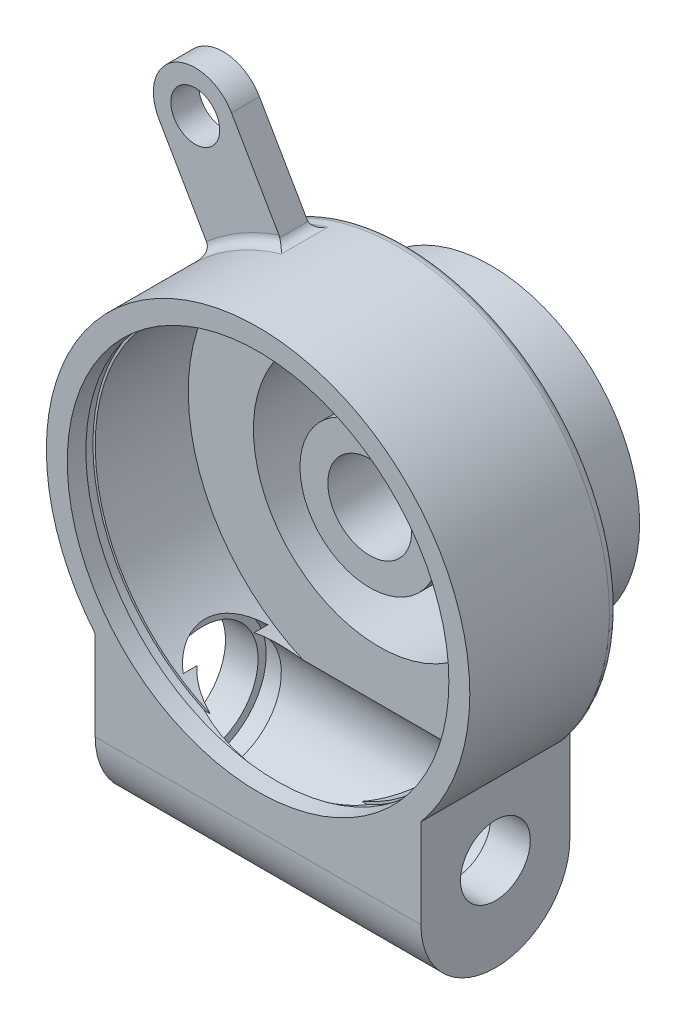
SolidWorks part; units mm, degrees
ref_plane "前视基准面" through (0, 0, 0) normal (0, 0, 1) x (1, 0, 0)
ref_plane "上视基准面" through (0, 0, 0) normal (0, 1, 0) x (1, 0, 0)
ref_plane "右视基准面" through (0, 0, 0) normal (1, 0, 0) x (0, 0, -1)
sketch "草图1" plane through (0, 0, 0) normal (0, 0, 1) x (1, 0, 0)
  circle A0 centre (0, 0) radius 45.5
  dimension "D1" = 91
extrude "凸台-拉伸1" add sketch "草图1" against normal blind 32
sketch "草图2" plane through (0, 0, -32) normal (0, 0, -1) x (-1, 0, 0)
  circle A0 centre (0, 0) radius 32
  dimension "D1" = 64
extrude "凸台-拉伸2" add sketch "草图2" along normal blind 18
sketch "草图3" plane through (0, 0, 0) normal (0, 0, 1) x (1, 0, 0)
  line L0 (0, 0) -> (-33.5, 58.0237) construction
  line L1 (-7.7942, -4.5) -> (-41.2942, 53.5237)
  line L2 (7.7942, 4.5) -> (-25.7058, 62.5237)
  line L3 (0, 0) -> (0, 77.4343) construction
  arc A0 (-7.7942, -4.5) -> (7.7942, 4.5) centre (0, 0) ccw
  arc A1 (-25.7058, 62.5237) -> (-41.2942, 53.5237) centre (-33.5, 58.0237) ccw
  arc A2 (-30.0947, 34.1256) -> (-14.5063, 43.1256) centre (0, 0) cw
  circle A3 centre (0, 0) radius 45.5 construction
  point P3 (-16.75, 29.0119)
  circle M3 centre (0, 0) radius 45.5
  dimension "D2" = 9
  dimension "D1" = 30
  dimension "D3" = 67
extrude "凸台-拉伸3" add sketch "草图3" along normal blind 6 from offset 26 contours L2 A1 L1 M3 offset against normal yes
sketch "草图4" plane through (0, 0, -20) normal (0, 0, 1) x (1, 0, 0)
  circle A0 centre (-33.5, 58.0237) radius 5.25
  dimension "D1" = 10.5
extrude "切除-拉伸1" cut sketch "草图4" against normal through all
sketch "草图5" plane through (0, 0, 0) normal (1, 0, 0) x (0, 0, -1)
  line L0 (16, -45.5) -> (16, -48.25) construction
  line L1 (0, -45.5) -> (32, -45.5) construction
  line L2 (32, -48.25) -> (16, -48.25) construction
  line L3 (32, -48.25) -> (32, -0.1888)
  line L4 (0, -48.25) -> (0, -0.1888)
  line L5 (32, -0.1888) -> (0, -0.1888)
  line L6 (16, -48.25) -> (0, -48.25) construction
  arc A0 (0, -48.25) -> (32, -48.25) centre (16, -48.25) ccw
  arc A1 (32, -48.25) -> (0, -48.25) centre (16, -48.25) ccw construction
  dimension "D1" = 32
  dimension "D2" = 48.25
extrude "凸台-拉伸4" add sketch "草图5" along normal mid plane 70
sketch "草图6" plane through (0, 0, 0) normal (0, 0, 1) x (1, 0, 0)
  circle A0 centre (0, 0) radius 41
  point P0 (0, 0)
  dimension "D1" = 82
extrude "切除-拉伸2" cut sketch "草图6" against normal blind 26
sketch "草图7" plane through (0, 0, 0) normal (0, 0, 1) x (1, 0, 0)
  circle A0 centre (0, 0) radius 41.5
  dimension "D1" = 83
extrude "切除-拉伸3" cut sketch "草图7" along normal blind 2 from offset 6 offset against normal yes
sketch "草图8" plane through (0, 0, -50) normal (0, 0, 1) x (1, 0, 0)
  circle A0 centre (0, 0) radius 27
  dimension "D1" = 54
extrude "切除-拉伸4" cut sketch "草图8" along normal up to next from offset 5
sketch "草图9" plane through (0, 0, -45) normal (0, 0, 1) x (1, 0, 0)
  circle A0 centre (0, 0) radius 15
  dimension "D1" = 30
extrude "凸台-拉伸5" add sketch "草图9" along normal blind 26 from surface at -5 starting at face at (-32, 0, -50)
sketch "草图10" plane through (0, 0, -50) normal (0, 0, -1) x (-1, 0, 0)
  circle A0 centre (0, 0) radius 9
  dimension "D1" = 18
extrude "切除-拉伸5" cut sketch "草图10" against normal up to next
chamfer "倒角1" distance 1 angle 45 1 edges at (-9, 0, -50)
sketch "草图11" plane through (-35, 0, 0) normal (-1, 0, 0) x (0, 0, 1)
  line L0 (-16, -64.25) -> (-16, -14.342) construction
  arc A0 (-32, -48.25) -> (0, -48.25) centre (-16, -48.25) ccw construction
  circle A1 centre (-16, -44.25) radius 13.75
  point P5 (-16, -44.25)
  dimension "D1" = 44.25
  dimension "D2" = 27.5
extrude "切除-拉伸6" cut sketch "草图11" along normal blind 5 from offset 12 offset against normal yes
sketch "草图12" plane through (-35, 0, 0) normal (-1, 0, 0) x (0, 0, 1)
  point P0 (-16, -44.25)
hole_wizard "M27 螺纹孔1" positions "草图12" profile "草图13" tap size "M27" standard "GB"
sketch "草图13" plane through (-35, -44.25, -16) normal (0, 1, 0) x (0, 0, 1)
  line L0 (0, 0) -> (0, 7)
  line L1 (0, 7) -> (12, 7)
  line L2 (12, 7) -> (12, 0)
  line L5 (12, 0) -> (0, 0)
  line L11 (0, -6.35) -> (0, 107.95) construction
  dimension "通孔螺纹孔钻头直径" = 24
  dimension "通孔螺纹孔钻头深度" = 7
cosmetic thread "孔螺纹线1" parameters "D2"=27
sketch "草图14" plane through (-23, 0, 0) normal (-1, 0, 0) x (0, 0, 1)
  circle A0 centre (-16, -44.25) radius 12
  circle A1 centre (-16, -44.25) radius 12 construction
  dimension "D1" = 24
extrude "切除-拉伸7" cut sketch "草图14" against normal blind 49.5
sketch "草图15" plane through (26.5, 0, 0) normal (-1, 0, 0) x (0, 0, 1)
  circle A0 centre (-16, -44.25) radius 7.5
  dimension "D1" = 15
extrude "切除-拉伸8" cut sketch "草图15" against normal up to next
fillet "圆角1" radius 2 4 edges at (-14.5063, 43.1256, -23) (-22.75, 39.4042, -26) (-30.0947, 34.1256, -23) (-22.75, 39.4042, -20)
fillet "圆角2" radius 2 2 edges at (-32, 0, -32) (0, 45.5, -32)
fillet "圆角3" radius 2 2 edges at (27, 0, -45) (15, 0, -45)
